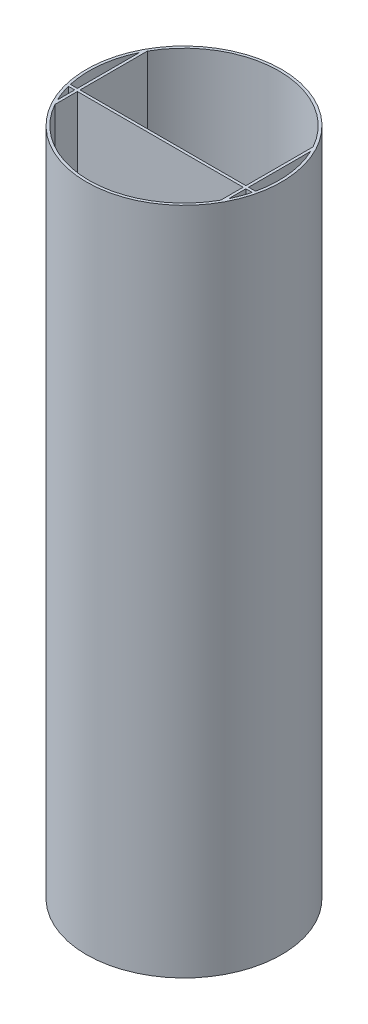
SolidWorks part; units mm, degrees
material "1060-O (SS)"
ref_plane "Front Plane" through (0, 0, 0) normal (0, 0, 1) x (1, 0, 0)
ref_plane "Top Plane" through (0, 0, 0) normal (0, 1, 0) x (1, 0, 0)
ref_plane "Right Plane" through (0, 0, 0) normal (1, 0, 0) x (0, 0, -1)
sketch "Sketch1" plane through (0, 0, 0) normal (0, 1, 0) x (1, 0, 0)
  line L0 (-71.2461, -16.8) -> (71.2461, -16.8) construction
  line L1 (0, 73.2) -> (0, -73.2) construction
  line L2 (-68.9391, -17.8) -> (-64.2, -17.8)
  line L3 (-69.4248, -15.8) -> (-64.2, -15.8)
  line L4 (-90.3982, -15.8) -> (78.569, -15.8) construction
  line L5 (-90.3982, -16.8) -> (78.569, -16.8) construction
  line L6 (-90.3982, -17.8) -> (78.569, -17.8) construction
  line L7 (-73.2, 0) -> (73.2, 0) construction
  line L8 (-63.2, 91.0884) -> (-63.2, -43.0499) construction
  line L9 (63.2, 36.9324) -> (63.2, -36.9324) construction
  line L10 (62.2, 34.6497) -> (62.2, -15.8)
  line L11 (-64.2, 30.7864) -> (-64.2, -15.8)
  line L12 (64.2, 30.7864) -> (64.2, -15.8)
  line L13 (-62.2, 34.6497) -> (-62.2, -15.8)
  line L14 (62.2, 98.8582) -> (62.2, -87.927) construction
  line L15 (63.2, 98.8582) -> (63.2, -87.927) construction
  line L16 (64.2, 98.8582) -> (64.2, -87.927) construction
  line L17 (64.2, -15.8) -> (69.4248, -15.8)
  line L18 (62.2, -17.8) -> (62.2, -34.6497)
  line L19 (64.2, -17.8) -> (68.9391, -17.8)
  line L20 (64.2, -17.8) -> (64.2, -30.7864)
  line L21 (-64.2, -35.1653) -> (-64.2, -87.927)
  line L22 (-64.2, 91.0884) -> (-64.2, -87.927) construction
  line L23 (-62.2, -38.5927) -> (-62.2, -87.927)
  line L24 (-62.2, 91.0884) -> (-62.2, -87.927) construction
  line L25 (-63.2, 91.0884) -> (-63.2, -87.927) construction
  line L26 (-62.2, -15.8) -> (62.2, -15.8)
  line L27 (-62.2, -17.8) -> (-62.2, -34.6497)
  line L28 (-62.2, -17.8) -> (62.2, -17.8)
  line L29 (-64.2, -17.8) -> (-64.2, -30.7864)
  circle A0 centre (0, 0) radius 73.2
  arc A1 (-68.9391, -17.8) -> (-64.2, -30.7864) centre (0, 0) ccw
  circle A2 centre (0, 0) radius 71.2 construction
  arc A3 (69.4248, -15.8) -> (64.2, 30.7864) centre (0, 0) ccw
  arc A4 (62.2, 34.6497) -> (-62.2, 34.6497) centre (0, 0) ccw
  arc A5 (64.2, -30.7864) -> (68.9391, -17.8) centre (0, 0) ccw
  arc A6 (-62.2, -34.6497) -> (62.2, -34.6497) centre (0, 0) ccw
  arc A7 (-64.2, 30.7864) -> (-69.4248, -15.8) centre (0, 0) ccw
  dimension "D1" = 146.4
  dimension "D3" = 90
  dimension "D6" = 10
  dimension "D7" = 10
  dimension "D2" = 2
  dimension "D4" = 1
  dimension "D5" = 1
  dimension "D8" = 1
  dimension "D9" = 1
extrude "Boss-Extrude1" add sketch "Sketch1" along normal blind 500 contours A0 A7 L11 L3 A6 L27 L28 L18 A5 L20 L19 A4 L10 L26 L13 A3 L17 L12 A1 L2 L29
sketch "Sketch3" plane through (0, 0, 0) normal (0, -1, 0) x (1, 0, 0)
  line L0 (0, 73.2) -> (0, -73.2) construction
  line L1 (-62.2, 17.8) -> (62.2, 17.8) construction
  line L2 (-62.2, 15.8) -> (62.2, 15.8) construction
  circle A0 centre (0, 0) radius 73.2
  circle A1 centre (0, -27.7) radius 2
  circle A2 centre (0, 41.5) radius 2
  arc A3 (62.2, 34.6497) -> (-62.2, 34.6497) centre (0, 0) ccw construction
  arc A4 (-62.2, -34.6497) -> (62.2, -34.6497) centre (0, 0) ccw construction
  point P9 (0, 71.2)
  point P10 (0, 17.8)
  point P14 (0, 15.8)
  point P17 (0, -71.2)
  dimension "D1" = 4
  dimension "D2" = 4
  dimension "D5" = 146.4
  dimension "D3" = 43.5
  dimension "D4" = 29.7
extrude "Boss-Extrude2" add sketch "Sketch3" along normal blind 2
ref_plane "Plane1" through (0, 40, 0) normal (0, 1, 0) x (1, 0, 0)
sketch "Sketch4" plane through (0, 40, 0) normal (0, 1, 0) x (1, 0, 0)
  line L0 (-62.2, -17.8) -> (-62.2, -34.6497) construction
  line L1 (62.2, -34.6497) -> (62.2, -17.8) construction
  line L2 (62.2, -17.8) -> (-62.2, -17.8) construction
  line L3 (62.2, -15.8) -> (62.2, 34.6497) construction
  line L4 (-62.2, 34.6497) -> (-62.2, -15.8) construction
  line L5 (-62.2, -15.8) -> (62.2, -15.8) construction
  line L6 (-62.2, -17.8) -> (-62.2, -34.6497)
  line L7 (62.2, -34.6497) -> (62.2, -17.8)
  line L8 (62.2, -17.8) -> (-62.2, -17.8)
  line L9 (62.2, -15.8) -> (62.2, 34.6497)
  line L10 (-62.2, 34.6497) -> (-62.2, -15.8)
  line L11 (-62.2, -15.8) -> (62.2, -15.8)
  arc A0 (-62.2, -34.6497) -> (62.2, -34.6497) centre (0, 0) ccw construction
  arc A1 (62.2, 34.6497) -> (-62.2, 34.6497) centre (0, 0) ccw construction
  arc A2 (-62.2, -34.6497) -> (62.2, -34.6497) centre (0, 0) ccw
  arc A3 (62.2, 34.6497) -> (-62.2, 34.6497) centre (0, 0) ccw
  circle A4 centre (0, 27.7) radius 2 construction
  circle A5 centre (0, 27.7) radius 2
  circle A6 centre (0, -41.5) radius 2 construction
  circle A7 centre (0, -41.5) radius 2
extrude "Boss-Extrude3" add sketch "Sketch4" along normal blind 2
sketch "Sketch6" plane through (0, 500, 0) normal (0, 1, 0) x (1, 0, 0)
  line L0 (62.2, -17.8) -> (-62.2, -17.8) construction
  line L1 (-62.2, -17.8) -> (-62.2, -34.6497) construction
  line L2 (62.2, -34.6497) -> (62.2, -17.8) construction
  line L3 (-62.2, -15.8) -> (62.2, -15.8) construction
  line L4 (62.2, -15.8) -> (62.2, 34.6497) construction
  line L5 (-62.2, 34.6497) -> (-62.2, -15.8) construction
  line L6 (62.2, -17.8) -> (-62.2, -17.8)
  line L7 (-62.2, -17.8) -> (-62.2, -34.6497)
  line L8 (62.2, -34.6497) -> (62.2, -17.8)
  line L9 (-62.2, -15.8) -> (62.2, -15.8)
  line L10 (62.2, -15.8) -> (62.2, 34.6497)
  line L11 (-62.2, 34.6497) -> (-62.2, -15.8)
  arc A0 (-62.2, -34.6497) -> (62.2, -34.6497) centre (0, 0) ccw construction
  arc A1 (62.2, 34.6497) -> (-62.2, 34.6497) centre (0, 0) ccw construction
  arc A2 (-62.2, -34.6497) -> (62.2, -34.6497) centre (0, 0) ccw
  arc A3 (62.2, 34.6497) -> (-62.2, 34.6497) centre (0, 0) ccw
